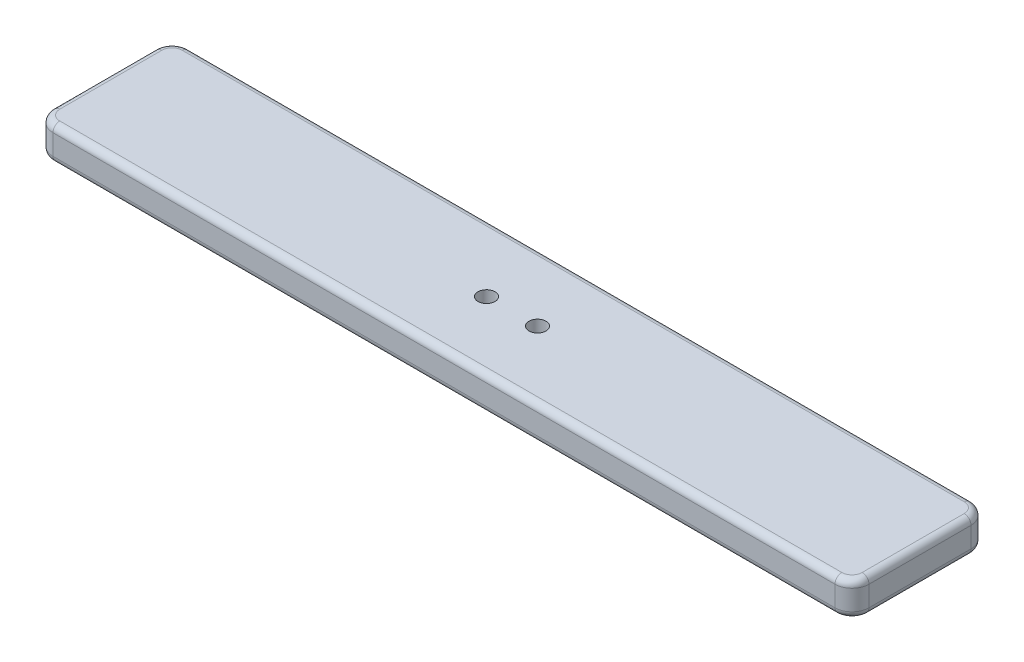
SolidWorks part; units mm, degrees
ref_plane "Front Plane" through (0, 0, 0) normal (0, 0, 1) x (1, 0, 0)
ref_plane "Top Plane" through (0, 0, 0) normal (0, 1, 0) x (1, 0, 0)
ref_plane "Right Plane" through (0, 0, 0) normal (1, 0, 0) x (0, 0, -1)
sketch "Sketch1" plane through (0, 0, 0) normal (0, 1, 0) x (1, 0, 0)
  line L1 (0, 0) -> (304.8, 0)
  line L2 (0, 0) -> (0, 50.8)
  line L3 (0, 50.8) -> (304.8, 50.8)
  line L4 (304.8, 0) -> (304.8, 50.8)
  dimension "D1" = 304.8
  dimension "D2" = 50.8
extrude "Boss-Extrude1" add sketch "Sketch1" along normal blind 12.7
sketch "Sketch2" plane through (0, 12.7, 0) normal (0, 1, 0) x (1, 0, 0)
  line L0 (0, 50.8) -> (304.8, 0) construction
  line L1 (304.8, 0) -> (304.8, 50.8) construction
  line L2 (304.8, 50.8) -> (0, 0) construction
  line L3 (152.4, 25.4) -> (152.4, 50025.4) construction
  circle A0 centre (142.875, 25.4) radius 3.175
  circle A1 centre (161.925, 25.4) radius 3.175
  point P4 (152.4, 25.4)
  dimension "D1" = 6.35
  dimension "D2" = 9.525
fillet "Fillet1" radius 6.35 4 edges at (304.8, 6.35, -50.8) (304.8, 6.35, 0) (0, 6.35, -50.8) (0, 6.35, 0)
fillet "Fillet2" radius 2.54 16 edges at (1.8599, 0, -48.9401) (0, 0, -25.4) (1.8599, 0, -1.8599) (152.4, 0, 0) (302.9401, 0, -1.8599) (304.8, 0, -25.4) (302.9401, 0, -48.9401) (152.4, 0, -50.8) (302.9401, 12.7, -1.8599) (152.4, 12.7, 0) (1.8599, 12.7, -1.8599) (0, 12.7, -25.4) (1.8599, 12.7, -48.9401) (152.4, 12.7, -50.8) (302.9401, 12.7, -48.9401) (304.8, 12.7, -25.4)
extrude "Cut-Extrude1" cut sketch "Sketch2" against normal through all
